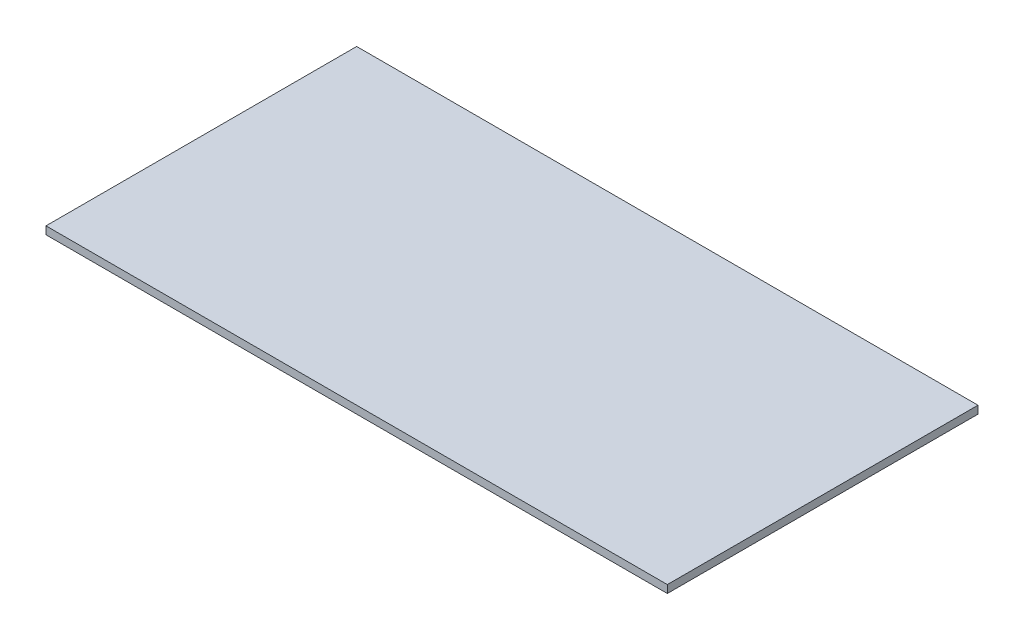
SolidWorks part; units mm, degrees
ref_plane "Front Plane" through (0, 0, 0) normal (0, 0, 1) x (1, 0, 0)
ref_plane "Top Plane" through (0, 0, 0) normal (0, 1, 0) x (1, 0, 0)
ref_plane "Right Plane" through (0, 0, 0) normal (1, 0, 0) x (0, 0, -1)
sketch "Sketch1" plane through (0, 0, 0) normal (0, 1, 0) x (1, 0, 0)
  line L1 (-200, -100) -> (200, -100)
  line L2 (-200, -100) -> (-200, 100)
  line L3 (-200, 100) -> (200, 100)
  line L4 (200, -100) -> (200, 100)
  line L5 (-200, -100) -> (200, 100) construction
  line L6 (-200, 100) -> (200, -100) construction
  point P0 (0, 0)
  dimension "D1" = 400
  dimension "D2" = 200
extrude "Boss-Extrude1" add sketch "Sketch1" along normal blind 5
